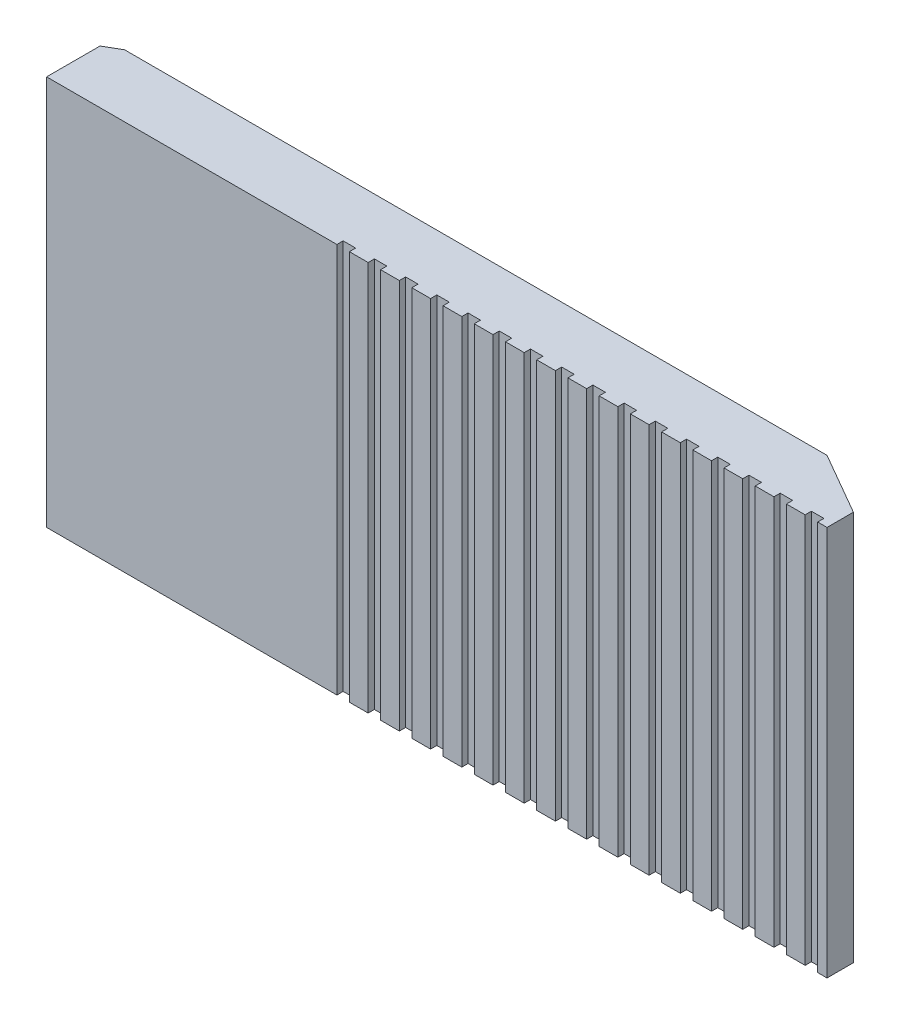
SolidWorks part; units mm, degrees
material "1060 Alloy"
ref_plane "Front Plane" through (0, 0, 0) normal (0, 0, 1) x (1, 0, 0)
ref_plane "Top Plane" through (0, 0, 0) normal (0, 1, 0) x (1, 0, 0)
ref_plane "Right Plane" through (0, 0, 0) normal (1, 0, 0) x (0, 0, -1)
sketch "Sketch1" plane through (0, 0, 0) normal (0, 0, 1) x (1, 0, 0)
  line L1 (-25, -12.5) -> (25, -12.5)
  line L2 (-25, -12.5) -> (-25, 12.5)
  line L3 (-25, 12.5) -> (25, 12.5)
  line L4 (25, -12.5) -> (25, 12.5)
  line L5 (-25, -12.5) -> (25, 12.5) construction
  line L6 (-25, 12.5) -> (25, -12.5) construction
  point P0 (0, 0)
  dimension "D1" = 25
  dimension "D2" = 50
extrude "Boss-Extrude1" add sketch "Sketch1" along normal blind 4
chamfer "Chamfer1" distance 4 angle 30 1 edges at (25, 0, 0)
sketch "Sketch2" plane through (0, 0, 0) normal (0, 0, -1) x (-1, 0, 0)
  line L0 (-25, 0) -> (-10, 0) construction
  line L1 (-25, -12.5) -> (-25, 12.5) construction
  line L3 (-15, -5) -> (-5, -5)
  line L4 (-15, -5) -> (-15, 5)
  line L5 (-15, 5) -> (-5, 5)
  line L6 (-5, -5) -> (-5, 5)
  line L7 (-15, -5) -> (-5, 5) construction
  line L8 (-15, 5) -> (-5, -5) construction
  dimension "D1" = 10
  dimension "D2" = 10
  dimension "D3" = 15
extrude "Boss-Extrude2" add sketch "Sketch2" along normal blind 5.5
sketch "Sketch3" plane through (0, 12.5, 0) normal (0, 1, 0) x (1, 0, 0)
  line L0 (25, -4) -> (-25, -4) construction
  line L1 (23.6, -4.4) -> (24.4, -4.4)
  line L2 (23.6, -4.4) -> (23.6, -3.6)
  line L3 (23.6, -3.6) -> (24.4, -3.6)
  line L4 (24.4, -4.4) -> (24.4, -3.6)
  line L5 (23.6, -4.4) -> (24.4, -3.6) construction
  line L6 (23.6, -3.6) -> (24.4, -4.4) construction
  line L7 (25, -4) -> (25, -2.3094) construction
  point P0 (24, -4)
  dimension "D1" = 0.8
  dimension "D2" = 0.8
  dimension "D3" = 1
extrude "Cut-Extrude1" cut sketch "Sketch3" against normal up to next
pattern_linear "LPattern1" count 16 spacing 2 along (-1, 0, 0) of "Cut-Extrude1"
chamfer "Chamfer2" distance 1 angle 30 1 edges at (-25, 0, 0)
